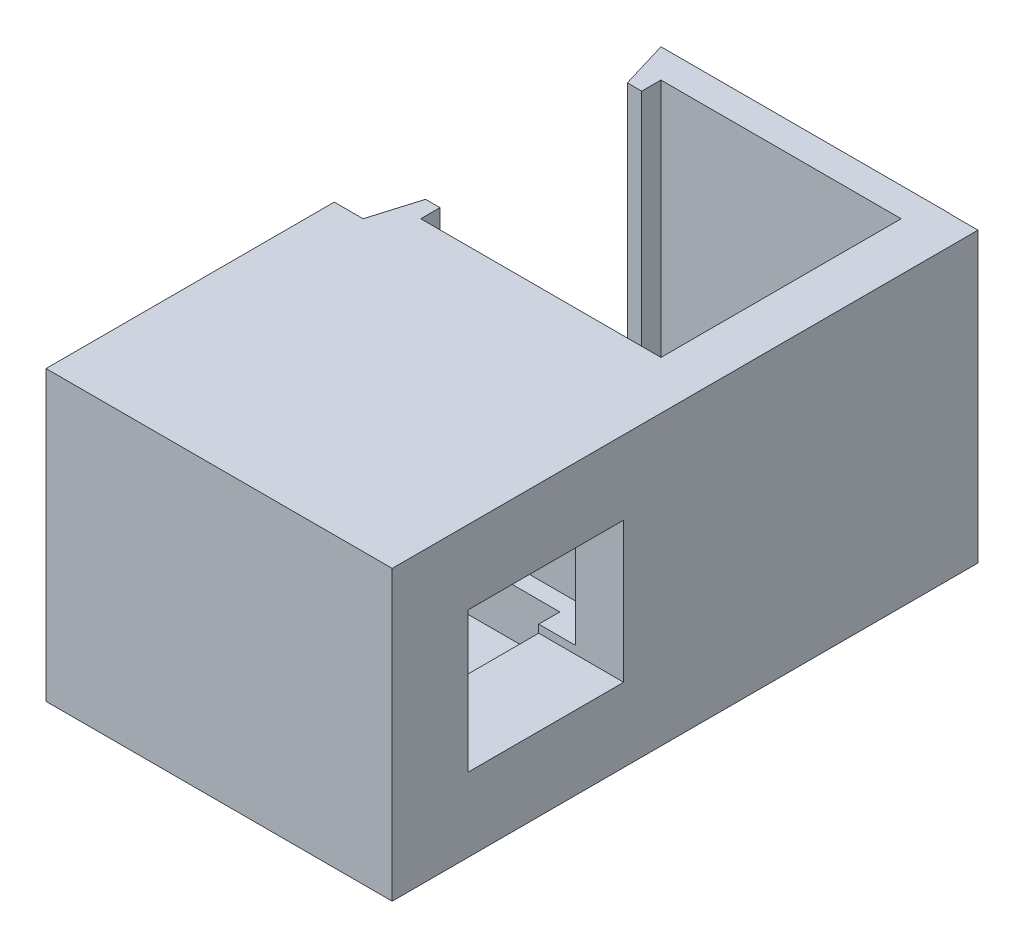
SolidWorks part; units mm, degrees
ref_plane "Спереди" through (0, 0, 0) normal (0, 0, 1) x (1, 0, 0)
ref_plane "Сверху" through (0, 0, 0) normal (0, 1, 0) x (1, 0, 0)
ref_plane "Справа" through (0, 0, 0) normal (1, 0, 0) x (0, 0, -1)
sketch "Эскиз1" plane through (0, 0, 0) normal (0, 1, 0) x (1, 0, 0)
  line L0 (-66.8258, 34.9697) -> (-66.8258, 29.9697)
  line L1 (-63.8258, 29.9697) -> (-63.8258, 31.9697)
  line L2 (-63.8258, 31.9697) -> (-38.8258, 31.9697)
  line L3 (-38.8258, 31.9697) -> (-38.8258, 6.9697)
  line L4 (-38.8258, 6.9697) -> (-63.8258, 6.9697)
  line L5 (-63.8258, 6.9697) -> (-63.8258, 8.9697)
  line L6 (-63.8258, 8.9697) -> (-66.8258, 8.9697)
  line L7 (-66.8258, 8.9697) -> (-66.8258, 3.9697)
  line L8 (-66.8258, 3.9697) -> (-22.1235, 3.9697)
  line L9 (-22.1235, 3.9697) -> (-36.579, 34.9697)
  line L10 (-36.579, 34.9697) -> (-66.8258, 34.9697)
  line L11 (-66.8258, 29.9697) -> (-63.8258, 29.9697)
  dimension "D1" = 25
  dimension "D2" = 25
  dimension "D3" = 25
  dimension "D4" = 155
  dimension "D5" = 3
  dimension "D6" = 3
  dimension "D7" = 3
  dimension "D8" = 3
  dimension "D9" = 2
  dimension "D10" = 2
extrude "Бобышка-Вытянуть1" add sketch "Эскиз1" along normal blind 30
sketch "Эскиз3" plane through (0, 0, 0) normal (0, -1, 0) x (1, 0, 0)
  line L0 (-66.8258, -3.9697) -> (-65.3258, -8.9697)
  line L1 (-63.8258, -8.9697) -> (-66.8258, -8.9697) construction
  line L2 (-65.3258, -8.9697) -> (-66.8258, -8.9697)
  line L3 (-66.8258, -8.9697) -> (-66.8258, -3.9697)
  line L4 (-66.8258, -29.9697) -> (-66.8258, -34.9697)
  line L5 (-66.8258, -34.9697) -> (-65.3258, -29.9697)
  line L6 (-66.8258, -29.9697) -> (-63.8258, -29.9697) construction
  line L7 (-65.3258, -29.9697) -> (-66.8258, -29.9697)
extrude "Вырез-Вытянуть4" cut sketch "Эскиз3" against normal through all
sketch "Эскиз7" plane through (0, 0, 0) normal (0, -1, 0) x (-1, 0, 0)
  line L1 (36.0076, 1.3029) -> (19.3993, 1.3029)
  line L2 (36.0076, 1.3029) -> (36.0076, 39.7765)
  line L3 (36.0076, 39.7765) -> (19.3993, 39.7765)
  line L4 (19.3993, 1.3029) -> (19.3993, 39.7765)
extrude "Вырез-Вытянуть14" cut sketch "Эскиз7" against normal through all
sketch "Эскиз8" plane through (0, 0, 0) normal (0, -1, 0) x (-1, 0, 0)
  line L0 (66.8258, 3.9697) -> (36.0076, 3.9697) construction
  line L1 (38.7989, 3.9697) -> (33.7989, 3.9697)
  line L2 (38.7989, 3.9697) -> (38.7989, 34.9383)
  line L3 (38.7989, 34.9383) -> (33.7989, 34.9383)
  line L4 (33.7989, 3.9697) -> (33.7989, 34.9383)
  dimension "D1" = 5
extrude "Бобышка-Вытянуть2" add sketch "Эскиз8" against normal up to surface (30 mm away) up to face at (-54.2963, 30, -20.5678)
sketch "Эскиз9" plane through (0, 0, -3.9697) normal (0, 0, 1) x (1, 0, 0)
  line L0 (-33.7989, 30) -> (-33.7989, 0) construction
  line L1 (-66.8258, 30) -> (-33.7989, 30)
  line L2 (-66.8258, 30) -> (-66.8258, 0)
  line L3 (-66.8258, 0) -> (-33.7989, 0)
  line L4 (-33.7989, 30) -> (-33.7989, 0)
extrude "Бобышка-Вытянуть3" add sketch "Эскиз9" along normal blind 30
sketch "Эскиз10" plane through (-33.7989, 0, 0) normal (1, 0, 0) x (0, 0, -1)
  line L0 (-26.0303, 15) -> (34.9383, 15) construction
  line L1 (-26.0303, 0) -> (-26.0303, 30) construction
  line L2 (34.9383, 30) -> (34.9383, 0) construction
  line L3 (-18.1303, 30) -> (-18.1303, 0) construction
  line L4 (34.9383, 30) -> (-26.0303, 30) construction
  line L5 (34.9383, 0) -> (-26.0303, 0) construction
  line L6 (5.9697, 30) -> (5.9697, 0) construction
  line L7 (-26.0303, 22.31) -> (34.9383, 22.31) construction
  line L8 (-26.0303, 7.685) -> (34.9383, 7.685) construction
  line L9 (-1.9303, 30) -> (-1.9303, 0) construction
  line L11 (-18.1303, 22.31) -> (-1.9303, 22.31)
  line L12 (-18.1303, 22.31) -> (-18.1303, 7.685)
  line L13 (-18.1303, 7.685) -> (-1.9303, 7.685)
  line L14 (-1.9303, 22.31) -> (-1.9303, 7.685)
  dimension "D1" = 7.685
  dimension "D2" = 7.69
  dimension "D3" = 32
  dimension "D4" = 7.9
  dimension "D5" = 7.9
extrude "Вырез-Вытянуть15" cut sketch "Эскиз10" against normal through all
sketch "Эскиз11" plane through (-66.8258, 0, 0) normal (-1, 0, 0) x (0, 0, 1)
  line L0 (18.1303, 14.9975) -> (-3.9697, 15) construction
  line L1 (18.1303, 22.31) -> (18.1303, 7.685) construction
  line L2 (-3.9697, 30) -> (-3.9697, 0) construction
  line L3 (-3.9697, 15) -> (26.0303, 15) construction
  line L4 (26.0303, 30) -> (26.0303, 0) construction
  line L6 (-0.2697, 26.5) -> (23.1303, 26.5)
  line L7 (-0.2697, 26.5) -> (-0.2697, 3.5)
  line L8 (-0.2697, 3.5) -> (23.1303, 3.5)
  line L9 (23.1303, 26.5) -> (23.1303, 3.5)
  dimension "D1" = 23.4
  dimension "D2" = 23
  dimension "D3" = 11.5
  dimension "D4" = 18.4
extrude "Вырез-Вытянуть16" cut sketch "Эскиз11" against normal offset from surface (24.1768 mm away) 8.85 up to face at (-33.7989, 14.9975, 10.0303)
sketch "Эскиз13" plane through (0, 0, 18.1303) normal (0, 0, -1) x (-1, 0, 0)
  line L0 (42.6489, 7.685) -> (33.7989, 7.685) construction
  line L1 (38.7989, 7.685) -> (42.1989, 7.685)
  line L2 (38.7989, 7.685) -> (38.7989, 22.31)
  line L3 (38.7989, 22.31) -> (42.1989, 22.31)
  line L4 (42.1989, 7.685) -> (42.1989, 22.31)
  line L5 (42.6489, 22.31) -> (33.7989, 22.31) construction
  line L6 (33.7989, 22.31) -> (33.7989, 7.685) construction
  dimension "D1" = 5
  dimension "D2" = 3.4
extrude "Вырез-Вытянуть17" cut sketch "Эскиз13" against normal blind 1.5
sketch "Эскиз14" plane through (-42.6489, 0, 0) normal (-1, 0, 0) x (0, 0, 1)
  line L0 (18.1303, 22.31) -> (18.1303, 26.5)
  line L1 (23.1303, 26.5) -> (-0.2697, 26.5) construction
  line L2 (18.1303, 26.5) -> (23.1303, 26.5)
  line L3 (23.1303, 26.5) -> (-0.2697, 26.5) construction
  line L4 (23.1303, 26.5) -> (23.1303, 3.5)
  line L5 (18.1303, 7.685) -> (18.1303, 3.5)
  line L6 (-0.2697, 3.5) -> (23.1303, 3.5) construction
  line L7 (18.1303, 3.5) -> (23.1303, 3.5)
  line L8 (18.1303, 22.31) -> (18.1303, 7.685)
extrude "Бобышка-Вытянуть4" add sketch "Эскиз14" along normal blind 5.5
sketch "Эскиз15" plane through (-66.8258, 0, 0) normal (-1, 0, 0) x (0, 0, 1)
  line L0 (-3.9697, 15) -> (26.0303, 15) construction
  line L1 (-3.9697, 30) -> (-3.9697, 0) construction
  line L2 (26.0303, 30) -> (26.0303, 0) construction
  line L3 (1.9303, 22.31) -> (1.9303, 7.685) construction
  line L4 (-2.0697, 21.5) -> (1.9303, 21.5)
  line L5 (-2.0697, 21.5) -> (-2.0697, 8.5)
  line L6 (-2.0697, 8.5) -> (1.9303, 8.5)
  line L7 (1.9303, 21.5) -> (1.9303, 8.5)
  dimension "D1" = 6.5
  dimension "D2" = 6.5
  dimension "D3" = 4
extrude "Вырез-Вытянуть18" cut sketch "Эскиз15" against normal offset from surface (28.0268 mm away) 5 up to face at (-33.7989, 14.9975, 10.0303)
sketch "Эскиз16" plane through (0, 0, -2.0697) normal (0, 0, 1) x (1, 0, 0)
  line L0 (-38.7989, 8.5) -> (-66.8258, 8.5) construction
  line L1 (-38.7989, 21.5) -> (-42.7989, 21.5)
  line L2 (-38.7989, 21.5) -> (-38.7989, 8.5)
  line L3 (-38.7989, 8.5) -> (-42.7989, 8.5)
  line L4 (-42.7989, 21.5) -> (-42.7989, 8.5)
  dimension "D1" = 4
extrude "Вырез-Вытянуть19" cut sketch "Эскиз16" against normal blind 1.5
sketch "Эскиз17" plane through (-66.8258, 0, 0) normal (-1, 0, 0) x (0, 0, 1)
  line L0 (-3.9697, 30) -> (26.0303, 30)
  line L1 (26.0303, 30) -> (26.0303, 0)
  line L2 (26.0303, 0) -> (-3.9697, 0)
  line L3 (-3.9697, 0) -> (-3.9697, 30)
  line L4 (-0.2697, 26.5) -> (23.1303, 26.5)
  line L5 (23.1303, 26.5) -> (-0.2697, 26.5) construction
  line L6 (18.1303, 26.5) -> (-0.2697, 26.5) construction
  line L7 (23.1303, 26.5) -> (23.1303, 3.5)
  line L8 (23.1303, 3.5) -> (-0.2697, 3.5)
  line L9 (-0.2697, 3.5) -> (-0.2697, 8.5)
  line L10 (-0.2697, 8.5) -> (-2.0697, 8.5)
  line L11 (-2.0697, 8.5) -> (-2.0697, 21.5)
  line L12 (-2.0697, 21.5) -> (-0.2697, 21.5)
  line L13 (-0.2697, 21.5) -> (-0.2697, 26.5)
extrude "Бобышка-Вытянуть5" add sketch "Эскиз17" along normal blind 3
